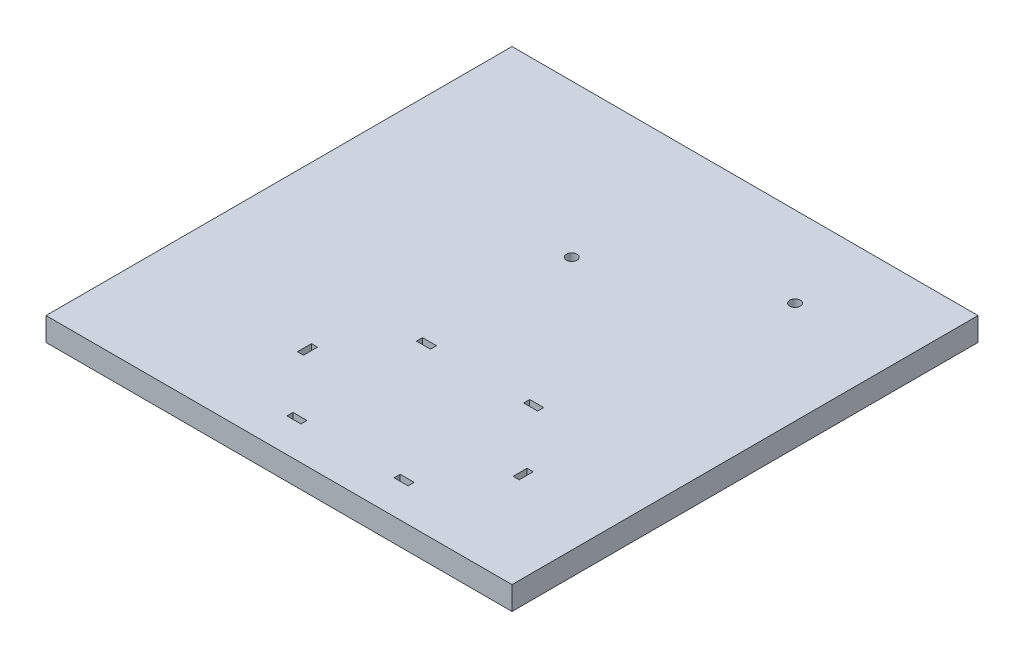
SolidWorks part; units mm, degrees
ref_plane "Front Plane" through (0, 0, 0) normal (0, 0, 1) x (1, 0, 0)
ref_plane "Top Plane" through (0, 0, 0) normal (0, 1, 0) x (1, 0, 0)
ref_plane "Right Plane" through (0, 0, 0) normal (1, 0, 0) x (0, 0, -1)
sketch "Sketch1" plane through (0, 0, 0) normal (0, 1, 0) x (1, 0, 0)
  line L0 (-66.0627, 0) -> (65.2437, 0) construction
  line L1 (-50, 50) -> (50, 50)
  line L2 (-50, 50) -> (-50, -50)
  line L3 (-50, -50) -> (50, -50)
  line L4 (50, 50) -> (50, -50)
  line L5 (7.5, -15) -> (7.5, -41.5) construction
  line L6 (-15, -15) -> (30, -15) construction
  line L7 (-15, -15) -> (-15, -41.5) construction
  line L8 (-15, -41.5) -> (30, -41.5) construction
  line L9 (30, -15) -> (30, -41.5) construction
  line L10 (-15.21, 35.09) -> (30, 35.09) construction
  line L11 (-15.21, 35.09) -> (-15.21, 15) construction
  line L12 (-15.21, 15) -> (30, 15) construction
  line L13 (30, 35.09) -> (30, 15) construction
  line L14 (-15.21, 35.09) -> (30, 15) construction
  line L15 (-15.21, 15) -> (30, 35.09) construction
  line L16 (-15, -28.25) -> (30, -28.25) construction
  line L17 (-5.5, -42.8) -> (-2.5, -42.8)
  line L18 (-5.5, -15) -> (-2.5, -15)
  line L19 (-5.5, -15) -> (-5.5, -13.7)
  line L20 (-5.5, -13.7) -> (-2.5, -13.7)
  line L21 (-2.5, -15) -> (-2.5, -13.7)
  line L22 (-2.5, -41.5) -> (-2.5, -42.8)
  line L23 (-5.5, -41.5) -> (-2.5, -41.5)
  line L24 (-5.5, -41.5) -> (-5.5, -42.8)
  line L25 (20.5, -15) -> (20.5, -13.7)
  line L26 (20.5, -13.7) -> (17.5, -13.7)
  line L27 (20.5, -15) -> (17.5, -15)
  line L28 (17.5, -15) -> (17.5, -13.7)
  line L29 (20.5, -41.5) -> (20.5, -42.8)
  line L30 (17.5, -41.5) -> (17.5, -42.8)
  line L31 (20.5, -41.5) -> (17.5, -41.5)
  line L32 (20.5, -42.8) -> (17.5, -42.8)
  line L33 (31.3, -29.75) -> (30, -29.75)
  line L34 (-16.3, -26.75) -> (-15, -26.75)
  line L35 (-16.3, -26.75) -> (-16.3, -29.75)
  line L36 (-16.3, -29.75) -> (-15, -29.75)
  line L37 (-15, -26.75) -> (-15, -29.75)
  line L38 (31.3, -26.75) -> (30, -26.75)
  line L39 (31.3, -26.75) -> (31.3, -29.75)
  line L40 (30, -26.75) -> (30, -29.75)
  circle A2 centre (28.07, 32.68) radius 1.13
  circle A3 centre (-4.44, 17.26) radius 1.13
  point P4 (50, 0)
  point P6 (0, 50)
  point P23 (7.395, 25.045)
  point P46 (-15, -28.25)
  dimension "D5" = 20
  dimension "D17" = 2.26
  dimension "D18" = 2.26
  dimension "D1" = 100
  dimension "D2" = 100
  dimension "D3" = 26.5
  dimension "D4" = 45
  dimension "D6" = 15
  dimension "D7" = 20
  dimension "D8" = 1.3
  dimension "D9" = 3
  dimension "D13" = 45.21
  dimension "D14" = 20.09
  dimension "D15" = 15
  dimension "D16" = 20
  dimension "D19" = 15.42
  dimension "D20" = 17.68
  dimension "D21" = 32.51
  dimension "D22" = 1.93
extrude "Boss-Extrude1" add sketch "Sketch1" along normal blind 5
